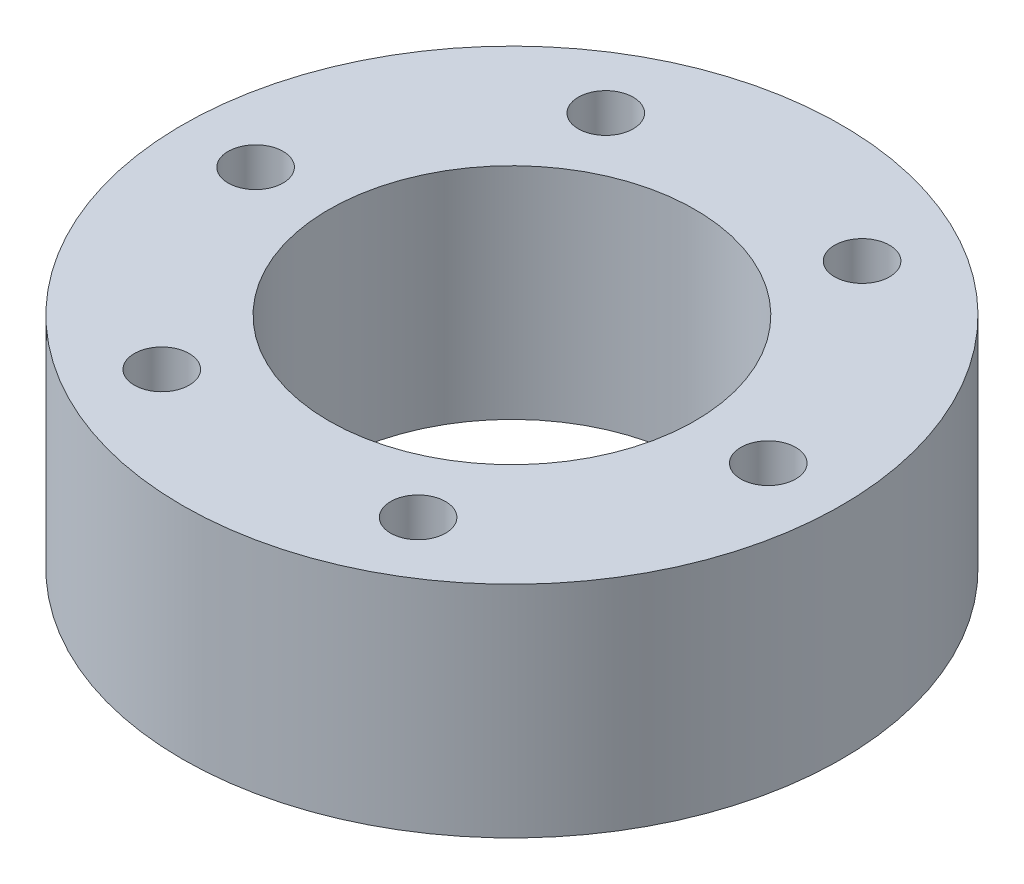
SolidWorks part; units mm, degrees
ref_plane "Front Plane" through (0, 0, 0) normal (0, 0, 1) x (1, 0, 0)
ref_plane "Top Plane" through (0, 0, 0) normal (0, 1, 0) x (1, 0, 0)
ref_plane "Right Plane" through (0, 0, 0) normal (1, 0, 0) x (0, 0, -1)
sketch "草图1" plane through (0, 0, 0) normal (0, 1, 0) x (1, 0, 0)
  circle A0 centre (0, 0) radius 10
  circle A1 centre (0, 0) radius 14 construction
  circle A2 centre (-14, 0) radius 1.5
  circle A3 centre (-7, 12.1244) radius 1.5
  circle A4 centre (7, 12.1244) radius 1.5
  circle A5 centre (14, 0) radius 1.5
  circle A6 centre (7, -12.1244) radius 1.5
  circle A7 centre (-7, -12.1244) radius 1.5
  circle A9 centre (0, 0) radius 18
  point P18 (0, 0)
  dimension "D1" = 28
  dimension "D2" = 3
  dimension "D4" = 20
  dimension "D5" = 4
  dimension "D3" = 6
extrude "凸台-拉伸1" add sketch "草图1" along normal blind 12
